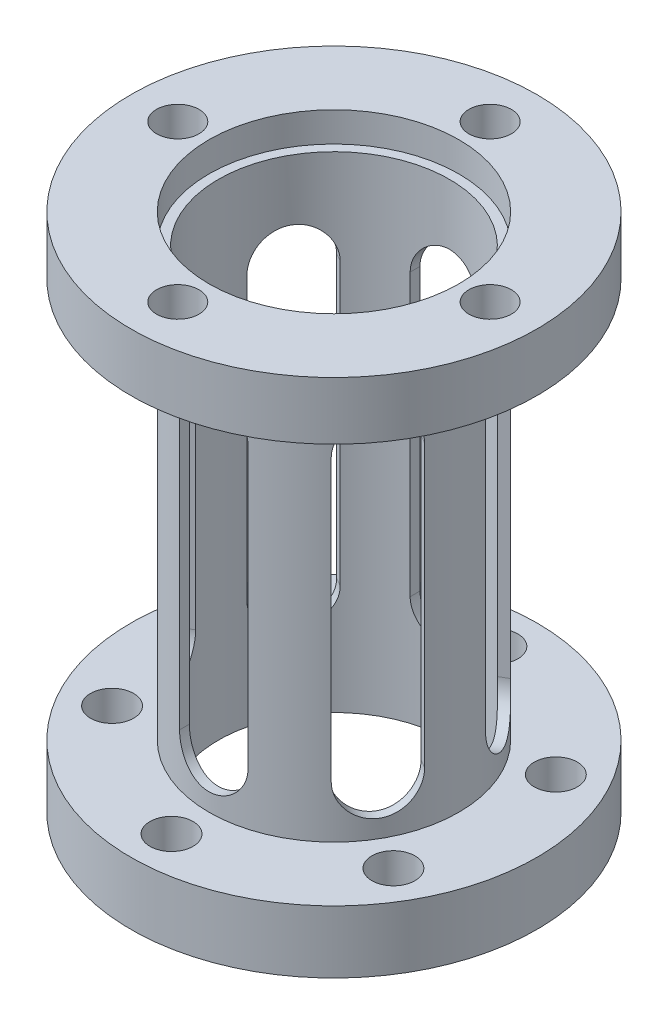
SolidWorks part; units mm, degrees
ref_plane "Front Plane" through (0, 0, 0) normal (0, 0, 1) x (1, 0, 0)
ref_plane "Top Plane" through (0, 0, 0) normal (0, 1, 0) x (1, 0, 0)
ref_plane "Right Plane" through (0, 0, 0) normal (1, 0, 0) x (0, 0, -1)
sketch "Sketch1" plane through (0, 0, 0) normal (0, 1, 0) x (1, 0, 0)
  circle A0 centre (0, 0) radius 16.51
extrude "Boss-Extrude1" add sketch "Sketch1" along normal blind 44.831
sketch "Sketch2" plane through (0, 44.831, 0) normal (0, 1, 0) x (1, 0, 0)
  circle A0 centre (0, 0) radius 9.398
extrude "Cut-Extrude1" cut sketch "Sketch2" against normal through all
sketch "Sketch3" plane through (0, 44.831, 0) normal (0, 1, 0) x (1, 0, 0)
  circle A0 centre (0, 0) radius 10.16
extrude "Cut-Extrude2" cut sketch "Sketch3" against normal blind 4.953
sketch "Sketch4" plane through (0, 44.831, 0) normal (0, 1, 0) x (1, 0, 0)
  circle A0 centre (0, 0) radius 12.7
  circle A1 centre (-12.7, 0) radius 1.7272
extrude "Cut-Extrude3" cut sketch "Sketch4" against normal blind 12.7 contours A1
ref_axis "Axis1" through (0, 0, 0) along (0, 1, 0)
pattern_circular "CirPattern1" count 4 over 360 about axis through (0, 0, 0) along (0, 1, 0) of "Cut-Extrude3"
sketch "Sketch5" plane through (0, 0, 0) normal (0, -1, 0) x (1, 0, 0)
  circle A0 centre (0, 0) radius 10.16
extrude "Cut-Extrude4" cut sketch "Sketch5" against normal blind 0.381
ref_plane "Plane1" through (0, -2.54, 0) normal (0, -1, 0) x (-1, 0, 0)
sketch "Sketch7" plane through (0, 0, 0) normal (0, 0, 1) x (1, 0, 0)
  line L1 (-19.197, 37.592) -> (-10.16, 37.592)
  line L2 (-19.197, 37.592) -> (-19.197, 5.08)
  line L3 (-19.197, 5.08) -> (-10.16, 5.08)
  line L4 (-10.16, 37.592) -> (-10.16, 5.08)
  point P4 (0, 0)
  point P5 (0, 0)
  point P6 (0, 0)
  point P7 (0, 0)
  point P8 (0, 0)
revolve "Cut-Revolve2" cut sketch "Sketch7" angle 360 about axis through (0, 0, 0) along (0, 1, 0)
sketch "Sketch9" plane through (0, 0, 0) normal (0, -1, 0) x (1, 0, 0)
  circle A0 centre (0, 0) radius 13.208
  circle A1 centre (0, -13.208) radius 1.7526
extrude "Cut-Extrude6" cut sketch "Sketch9" against normal blind 10.16 contours A1
pattern_circular "CirPattern3" count 6 over 360 about axis through (0, 0, 0) along (0, 1, 0) of "Cut-Extrude6"
ref_plane "Plane2" through (0, 0, 16.51) normal (0, 0, 1) x (1, 0, 0)
sketch "Sketch12" plane through (0, 0, 16.51) normal (0, 0, 1) x (1, 0, 0)
  line L0 (0, 32.1645) -> (0, 9.3045) construction
  line L1 (0, 0) -> (0, 39.751) construction
  line L2 (2.7801, 32.1645) -> (2.7801, 9.3045)
  line L3 (-2.7801, 32.1645) -> (-2.7801, 9.3045)
  arc A0 (2.7801, 32.1645) -> (-2.7801, 32.1645) centre (0, 32.1645) ccw
  arc A1 (-2.7801, 9.3045) -> (2.7801, 9.3045) centre (0, 9.3045) ccw
  point P4 (0, 20.7345)
  point P10 (0, 0)
  point P11 (0, 0)
  point P12 (0, 0)
  point P13 (0, 0)
extrude "Cut-Extrude7" cut sketch "Sketch12" against normal blind 15.24
pattern_circular "CirPattern4" count 6 over 360 about axis through (0, 0, 0) along (0, 1, 0) of "Cut-Extrude7", "Cut-Revolve2"
sketch "Sketch13" plane through (0, 44.831, 0) normal (0, 1, 0) x (1, 0, 0)
  circle A0 centre (0, 0) radius 16.51
extrude "Cut-Extrude8" cut sketch "Sketch13" against normal blind 2.54
